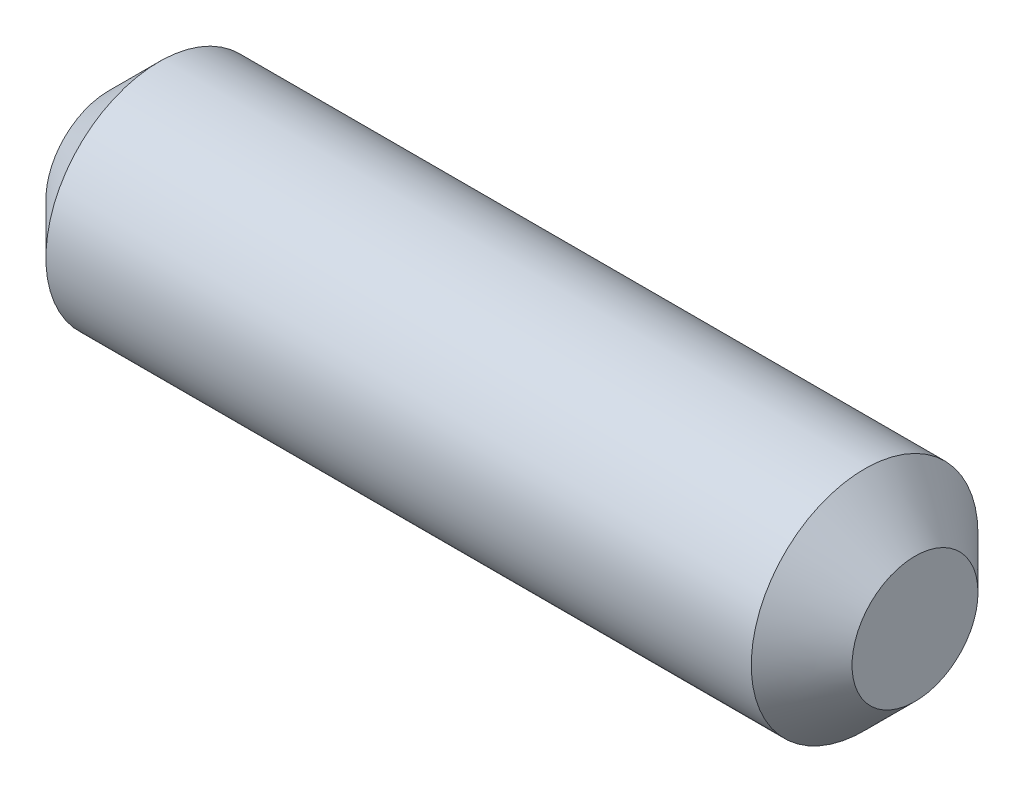
SolidWorks part; units mm, degrees
ref_plane "Front Plane" through (0, 0, 0) normal (0, 0, 1) x (1, 0, 0)
ref_plane "Top Plane" through (0, 0, 0) normal (0, 1, 0) x (1, 0, 0)
ref_plane "Right Plane" through (0, 0, 0) normal (1, 0, 0) x (0, 0, -1)
sketch "Sketch1" plane through (0, 0, 0) normal (0, 0, 1) x (1, 0, 0)
  line L0 (0, 0) -> (16, 0)
  dimension "D1" = 16
sweep "Sweep1" add path "Sketch1" circular profile diameter 4.5 parameters "D3"=4.5
chamfer "Chamfer1" distance 1 angle 45 2 edges at (0, 0, -2.25) (16, 0, -2.25)
scale "Scale1" scale about centroid uniform scaling yes scale factor 0.8
